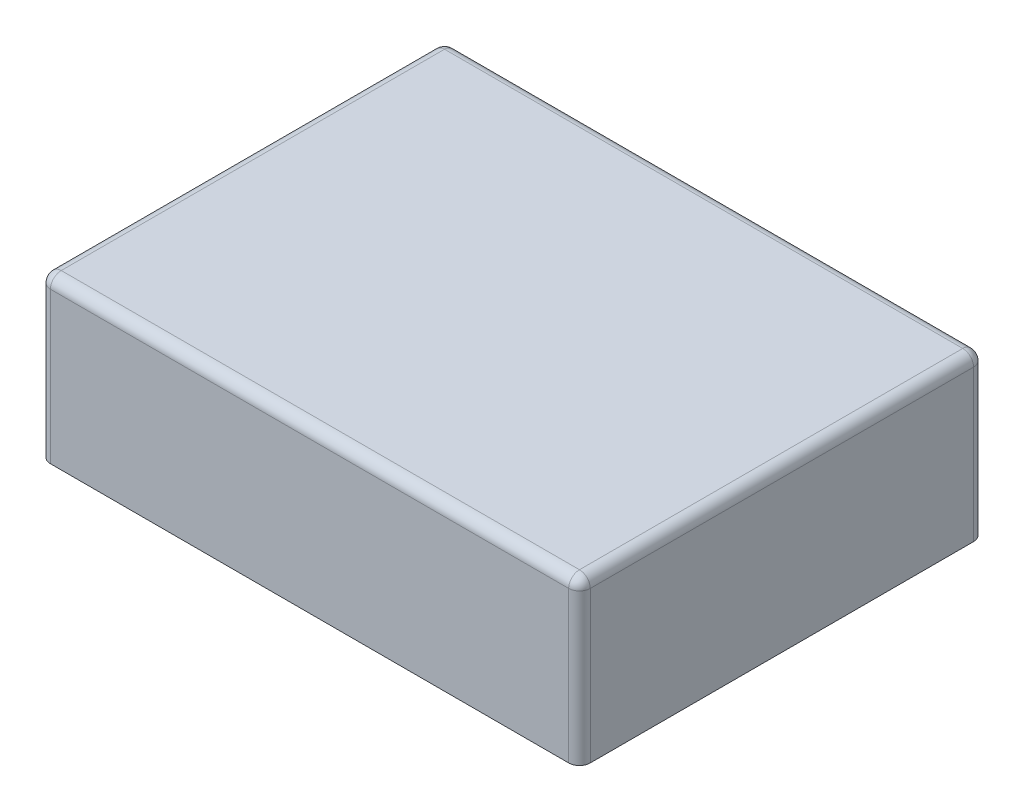
SolidWorks part; units mm, degrees
ref_plane "Front Plane" through (0, 0, 0) normal (0, 0, 1) x (1, 0, 0)
ref_plane "Top Plane" through (0, 0, 0) normal (0, 1, 0) x (1, 0, 0)
ref_plane "Right Plane" through (0, 0, 0) normal (1, 0, 0) x (0, 0, -1)
sketch "Sketch1" plane through (0, 0, 0) normal (0, 1, 0) x (1, 0, 0)
  line L1 (-50, 37.5) -> (50, 37.5)
  line L2 (-50, 37.5) -> (-50, -37.5)
  line L3 (-50, -37.5) -> (50, -37.5)
  line L4 (50, 37.5) -> (50, -37.5)
  line L5 (-50, 37.5) -> (50, -37.5) construction
  line L6 (-50, -37.5) -> (50, 37.5) construction
  point P0 (0, 0)
  dimension "D1" = 100
  dimension "D2" = 75
extrude "Boss-Extrude1" add sketch "Sketch1" along normal blind 30
shell "Shell1" thickness 2
sketch "Sketch2" plane through (0, 30, 0) normal (0, 1, 0) x (1, 0, 0)
  line L0 (0, 0) -> (-57.0696, 0) construction
  line L2 (9.4786, 16.6) -> (-27.8214, 16.6)
  line L3 (9.4786, 16.6) -> (9.4786, -16.6)
  line L4 (9.4786, -16.6) -> (-27.8214, -16.6)
  line L5 (-27.8214, 16.6) -> (-27.8214, -16.6)
  line L6 (9.4786, 16.6) -> (-27.8214, -16.6) construction
  line L7 (9.4786, -16.6) -> (-27.8214, 16.6) construction
  point P3 (-9.1714, 0)
  dimension "D1" = 33.2
  dimension "D2" = 37.3
fillet "Fillet1" radius 2 8 edges at (0, 30, 37.5) (-50, 30, 0) (0, 30, -37.5) (50, 30, 0) (-50, 15, -37.5) (50, 15, -37.5) (50, 15, 37.5) (-50, 15, 37.5)
